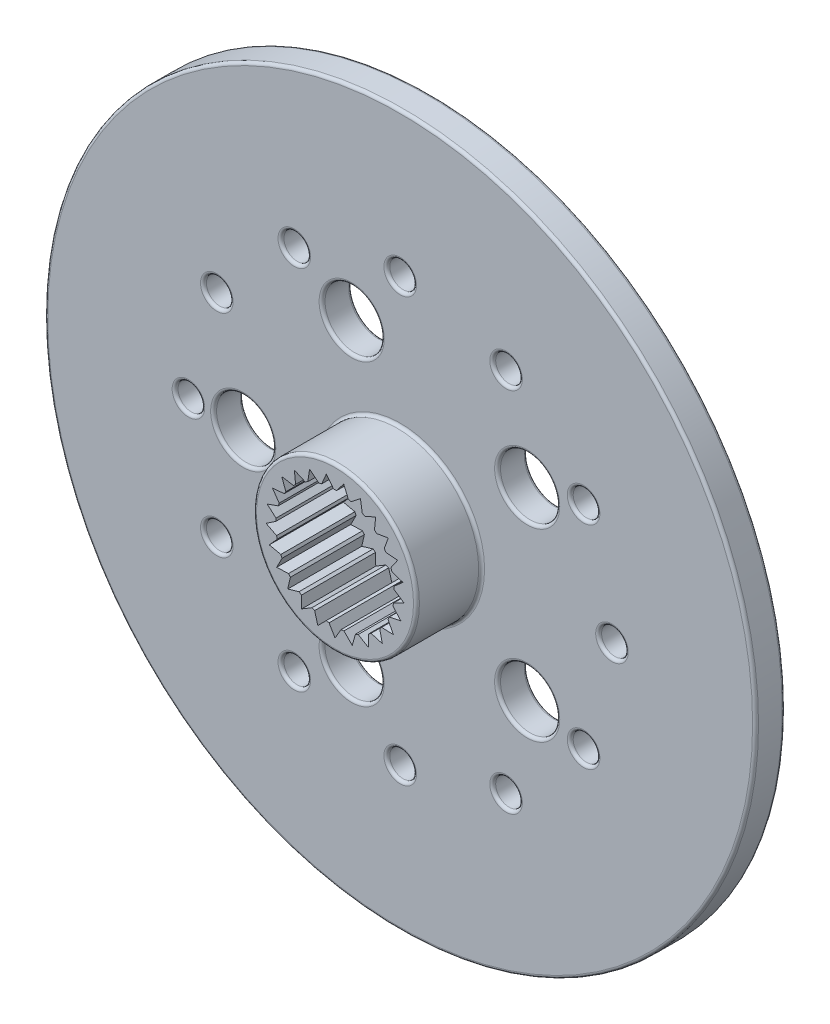
SolidWorks part; units mm, degrees
material "ABS"
ref_plane "Plan de face" through (0, 0, 0) normal (0, 0, 1) x (1, 0, 0)
ref_plane "Plan de dessus" through (0, 0, 0) normal (0, 1, 0) x (1, 0, 0)
ref_plane "Plan de droite" through (0, 0, 0) normal (1, 0, 0) x (0, 0, -1)
sketch "Esquisse1" plane through (0, 0, 0) normal (0, 0, 1) x (1, 0, 0)
  line L0 (-25.8199, 1.564) -> (18.3852, 1.564) construction
  line L5 (0, 0) -> (0, -2.75) construction
  circle A0 centre (0, 0) radius 2.75
  circle A1 centre (0, 0) radius 12
  dimension "D1" = 5.5
  dimension "D2" = 24
extrude "Boss.-Extru.1" add sketch "Esquisse1" along normal blind 1
sketch "Esquisse2" plane through (0, 0, 1) normal (0, 0, 1) x (1, 0, 0)
  circle A0 centre (0, 0) radius 2.75
  dimension "D1" = 5.5
extrude "Boss.-Extru.2" add sketch "Esquisse2" along normal offset from surface (2.2 mm away) 3.2 up to face at (12, 0, 0)
sketch "Esquisse3" plane through (0, 0, 3.2) normal (0, 0, 1) x (1, 0, 0)
  circle A0 centre (0, 0) radius 2
  dimension "D1" = 4
extrude "Enlèv. mat.-Extru.1" cut sketch "Esquisse3" against normal blind 2.5
sketch "Sketch1" plane through (0, 0, 3.2) normal (0, 0, 1) x (1, 0, 0)
  line L0 (0, 0) -> (0, -2) construction
  line L1 (0, 0) -> (0.2007, -1.9899) construction
  line L2 (0, 0) -> (-0.2007, -1.9899) construction
  line L3 (0.2007, -1.9899) -> (0, -2.334)
  line L4 (0, -2.334) -> (-0.2007, -1.9899)
  circle A0 centre (0, 0) radius 2 construction
  circle A1 centre (0, 0) radius 2 construction
  arc A2 (-0.2007, -1.9899) -> (0.2007, -1.9899) centre (0, 0) ccw
  circle A3 centre (0, 0) radius 2.334 construction
  dimension "D3" = 4.668
  dimension "D1" = 5.76
  dimension "D2" = 5.76
extrude "Cut-Extrude1" cut sketch "Sketch1" against normal up to surface (2.5 mm away) contours L4 A2 L3 up to face at (2, 0, 0.7)
pattern_circular "CirPattern1" count 25 over 360 about axis through (0, 0, 0) along (0, 0, 1) of "Cut-Extrude1"
sketch "Esquisse4" plane through (0, 0, 0) normal (0, 0, -1) x (-1, 0, 0)
  circle A0 centre (0, 0) radius 1.6
  dimension "D1" = 3.2
extrude "Enlèv. mat.-Extru.2" cut sketch "Esquisse4" against normal blind 0.4
sketch "Esquisse5" plane through (0, 0, 0.4) normal (0, 0, -1) x (-1, 0, 0)
  circle A0 centre (0, 0) radius 0.85
  dimension "D1" = 1.7
extrude "Enlèv. mat.-Extru.3" cut sketch "Esquisse5" against normal blind 4.8
hole_wizard "Ø0.9 (0.9) Diameter Hole1" positions "Sketch3" profile "Sketch2" hole size "Ø0.9" standard "ANSI Metric" end condition through all
sketch "Sketch3" plane through (0, 0, 0) normal (0, 0, -1) x (-1, 0, 0)
  line L2 (7.15, 0) -> (-7.15, 0) construction
  point P21 (7.15, 0)
  dimension "D1" = 14.3
sketch "Sketch2" plane through (-7.15, 0, 0) normal (1, 0, 0) x (0, 1, 0)
  line L0 (0, 0) -> (0, 3.2)
  line L1 (0, 3.2) -> (0.45, 3.2)
  line L2 (0.45, 3.2) -> (0.45, 0)
  line L5 (0.45, 0) -> (0, 0)
  line L11 (0, -6.35) -> (0, 107.95) construction
  dimension "Thru Hole Dia." = 0.9
  dimension "Thru Hole Depth" = 3.2
pattern_circular "CirPattern2" count 12 over 360 about axis through (0, 0, 0) along (0, 0, 1) of "Ø0.9 (0.9) Diameter Hole1"
hole_wizard "Ø2.0 (2) Diameter Hole1" positions "Sketch5" profile "Sketch4" hole size "Ø2.0" standard "ANSI Metric" end condition through all
sketch "Sketch5" plane through (0, 0, 0) normal (0, 0, -1) x (-1, 0, 0)
  line L0 (5.3, 0) -> (-5.3, 0) construction
  point P0 (5.3, 0)
  dimension "D1" = 10.6
sketch "Sketch4" plane through (-5.3, 0, 0) normal (1, 0, 0) x (0, 1, 0)
  line L0 (0, 0) -> (0, 3.2)
  line L1 (0, 3.2) -> (1, 3.2)
  line L2 (1, 3.2) -> (1, 0)
  line L5 (1, 0) -> (0, 0)
  line L11 (0, -6.35) -> (0, 107.95) construction
  dimension "Thru Hole Dia." = 2
  dimension "Thru Hole Depth" = 3.2
pattern_circular "CirPattern3" count 5 over 360 about axis through (0, 0, 0) along (0, 0, 1) of "Ø2.0 (2) Diameter Hole1"
fillet "Fillet1" radius 0.1 39 edges at (12, 0, 1) (2.75, 0, 1) (-6.7, 0, 1) (-5.7421, 3.575, 1) (-3.125, 6.1921, 1) (0.45, 7.15, 1) (4.025, 6.1921, 1) (6.6421, 3.575, 1) (7.6, 0, 1) (6.6421, -3.575, 1) (4.025, -6.1921, 1) (0.45, -7.15, 1) (-3.125, -6.1921, 1) (-5.7421, -3.575, 1) (-4.3, 0, 1) (-0.6378, 5.0406, 1) (5.2878, 3.1153, 1) (5.2878, -3.1153, 1) (-0.6378, -5.0406, 1) (-0.45, 7.15, 0) (12, 0, 0) (-1.6, 0, 0) (-7.6, 0, 0) (-6.6421, 3.575, 0) (-4.025, 6.1921, 0) (3.125, 6.1921, 0) (5.7421, 3.575, 0) (6.7, 0, 0) (5.7421, -3.575, 0) (3.125, -6.1921, 0) (-0.45, -7.15, 0) (-4.025, -6.1921, 0) (-6.6421, -3.575, 0) (-6.3, 0, 0) (-2.6378, 5.0406, 0) (3.2878, 3.1153, 0) (3.2878, -3.1153, 0) (-2.6378, -5.0406, 0) (2.75, 0, 3.2)
equation "\"D2@Sketch1\"=\"D1@Sketch1\""
